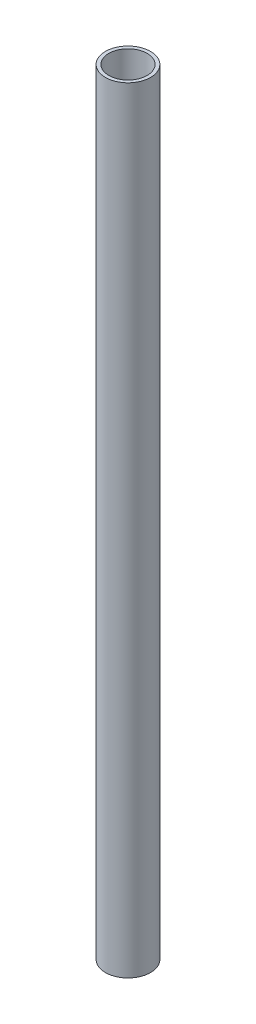
SolidWorks part; units mm, degrees
ref_plane "前视基准面" through (0, 0, 0) normal (0, 0, 1) x (1, 0, 0)
ref_plane "上视基准面" through (0, 0, 0) normal (0, 1, 0) x (1, 0, 0)
ref_plane "右视基准面" through (0, 0, 0) normal (1, 0, 0) x (0, 0, -1)
other "Configuration Table"
sketch "草图1" plane through (0, 0, 0) normal (0, 1, 0) x (1, 0, 0)
  circle A14 centre (0, 0) radius 16
  circle A15 centre (0, 0) radius 13.6
  dimension "D1" = 32
  dimension "D2" = 2.4
extrude "凸台-拉伸1" add sketch "草图1" along normal blind 550
